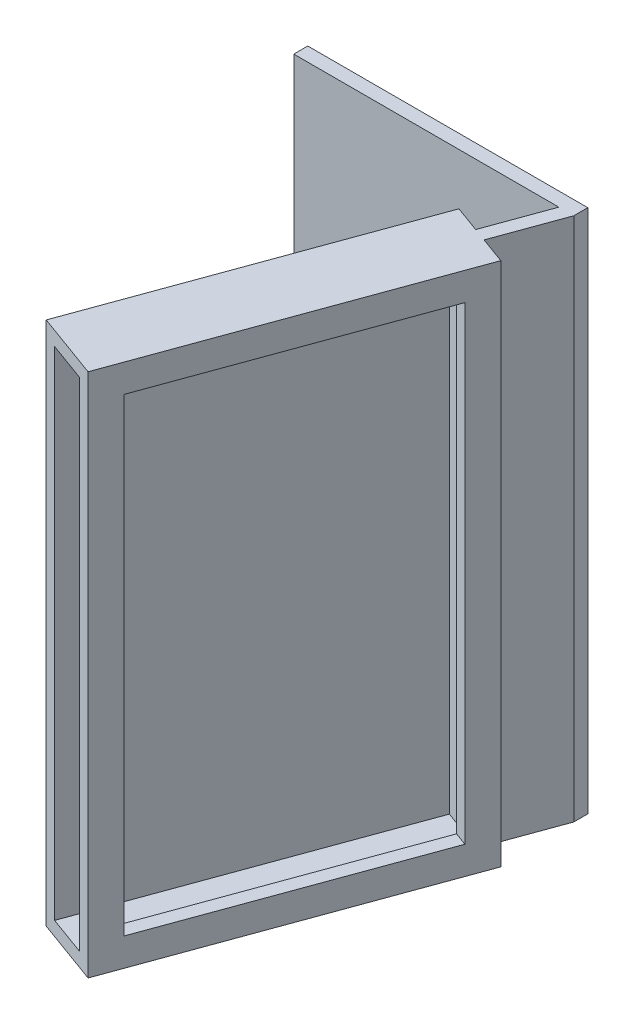
SolidWorks part; units mm, degrees
ref_plane "Front Plane" through (0, 0, 0) normal (1, 0, 0) x (0, 1, 0)
ref_plane "Top Plane" through (0, 0, 0) normal (0, 0, 1) x (0, 1, 0)
ref_plane "Right Plane" through (0, 0, 0) normal (0, 1, 0) x (-1, 0, 0)
sketch "Sketch1" plane through (0, 0, 0) normal (0, 0, 1) x (0, 1, 0)
  line L1 (0, 0) -> (95.25, 0)
  line L2 (0, 0) -> (0, 50.8)
  line L3 (0, 50.8) -> (95.25, 50.8)
  line L4 (95.25, 0) -> (95.25, 50.8)
  dimension "D1" = 95.25
  dimension "D2" = 50.8
extrude "Boss-Extrude1" add sketch "Sketch1" along normal blind 2.54
sketch "Sketch2" plane through (0, 95.25, 0) normal (0, 1, 0) x (-1, 0, 0)
  line L0 (0, 2.54) -> (4.3437, 14.4741)
  line L1 (4.3437, 14.4741) -> (6.7305, 13.6054)
  line L2 (6.7305, 13.6054) -> (2.703, 2.54)
  line L3 (0, 2.54) -> (50.8, 2.54) construction
  line L4 (2.703, 2.54) -> (0, 2.54)
  dimension "D1" = 2.54
  dimension "D2" = 12.7
  dimension "D3" = 70
extrude "Boss-Extrude2" add sketch "Sketch2" against normal up to surface (95.25 mm away) up to face at (-25.4, 0, 1.27)
sketch "Sketch3" plane through (-5.16, 0, 14.177) normal (-0.342, 0, 0.9397) x (0.9397, 0, 0.342)
  line L1 (-6.7513, 95.25) -> (5.9487, 95.25)
  line L2 (-6.7513, 95.25) -> (-6.7513, 0)
  line L3 (-6.7513, 0) -> (5.9487, 0)
  line L4 (5.9487, 95.25) -> (5.9487, 0)
  line L6 (-0.4013, 95.25) -> (-0.4013, 0) construction
  line L9 (-1.6713, 95.25) -> (0.8687, 95.25) construction
  line L10 (0.8687, 0) -> (-1.6713, 0) construction
  point P13 (-0.4013, 0)
  point P14 (-0.4013, 95.25)
  dimension "D1" = 12.7
extrude "Boss-Extrude3" add sketch "Sketch3" along normal blind 2.54
sketch "Sketch4" plane through (-6.0287, 0, 16.5638) normal (-0.342, 0, 0.9397) x (0.9397, 0, 0.342)
  line L1 (-6.7513, 95.25) -> (5.9487, 95.25)
  line L2 (-6.7513, 95.25) -> (-6.7513, 0)
  line L3 (-6.7513, 0) -> (5.9487, 0)
  line L4 (5.9487, 95.25) -> (5.9487, 0)
  line L5 (-4.2113, 92.71) -> (3.4087, 92.71)
  line L6 (-4.2113, 92.71) -> (-4.2113, 2.54)
  line L7 (-4.2113, 2.54) -> (3.4087, 2.54)
  line L8 (3.4087, 92.71) -> (3.4087, 2.54)
  dimension "D2" = 2.54
  dimension "D3" = 2.54
  dimension "D4" = 2.54
extrude "Boss-Extrude4" add sketch "Sketch4" along normal blind 55.88
sketch "Sketch5" plane through (5.59, 0, 2.0346) normal (0.9397, 0, 0.342) x (0, 1, 0)
  line L0 (0, 73.5068) -> (0, 15.0868) construction
  line L1 (5.08, 68.4268) -> (90.17, 68.4268)
  line L2 (5.08, 68.4268) -> (5.08, 20.1668)
  line L3 (5.08, 20.1668) -> (90.17, 20.1668)
  line L4 (90.17, 68.4268) -> (90.17, 20.1668)
  line L5 (0, 73.5068) -> (95.25, 73.5068) construction
  line L6 (95.25, 73.5068) -> (95.25, 15.0868) construction
  line L7 (0, 15.0868) -> (95.25, 15.0868) construction
  dimension "D1" = 5.08
  dimension "D2" = 5.08
  dimension "D3" = 5.08
  dimension "D4" = 5.08
extrude "Cut-Extrude1" cut sketch "Sketch5" against normal up to next
equation "\"in-w\"= 3.5"
equation "\"in-h\"=2"
equation "\"thicknes\"=0.2"
equation "\"wall-t\"= \"thicknes\" / 2"
equation "\"tot-w\"= \"in-w\" + .15 + 0.1"
equation "\"tot-h\"= \"in-h\" * 2"
equation "\"D1@Sketch1\"=\"tot-w\""
equation "\"D2@Sketch1\"=\"in-h\""
equation "\"D1@Boss-Extrude1\"=\"wall-t\""
equation "\"D1@Sketch2\"=\"wall-t\""
equation "\"D2@Sketch2\"=\"frame-h\""
equation "\"angle\"= 70"
equation "\"D3@Sketch2\"=\"angle\""
equation "\"frame-h\"= 0.5"
equation "\"D1@Sketch3\"=\"thicknes\" + 2 * \"wall-t\" +0.1"
equation "\"D1@Sketch4\"=\"wall-t\""
equation "\"D2@Sketch4\"=\"wall-t\""
equation "\"D3@Sketch4\"=\"wall-t\""
equation "\"D4@Sketch4\"=\"wall-t\""
equation "\"D1@Boss-Extrude4\"=\"in-h\"+2 * \"wall-t\""
equation "\"D1@Sketch5\"= 2 * \"wall-t\""
equation "\"D2@Sketch5\"= 2 * \"wall-t\""
equation "\"D3@Sketch5\"= 2 * \"wall-t\""
equation "\"D4@Sketch5\"= 2 * \"wall-t\""
